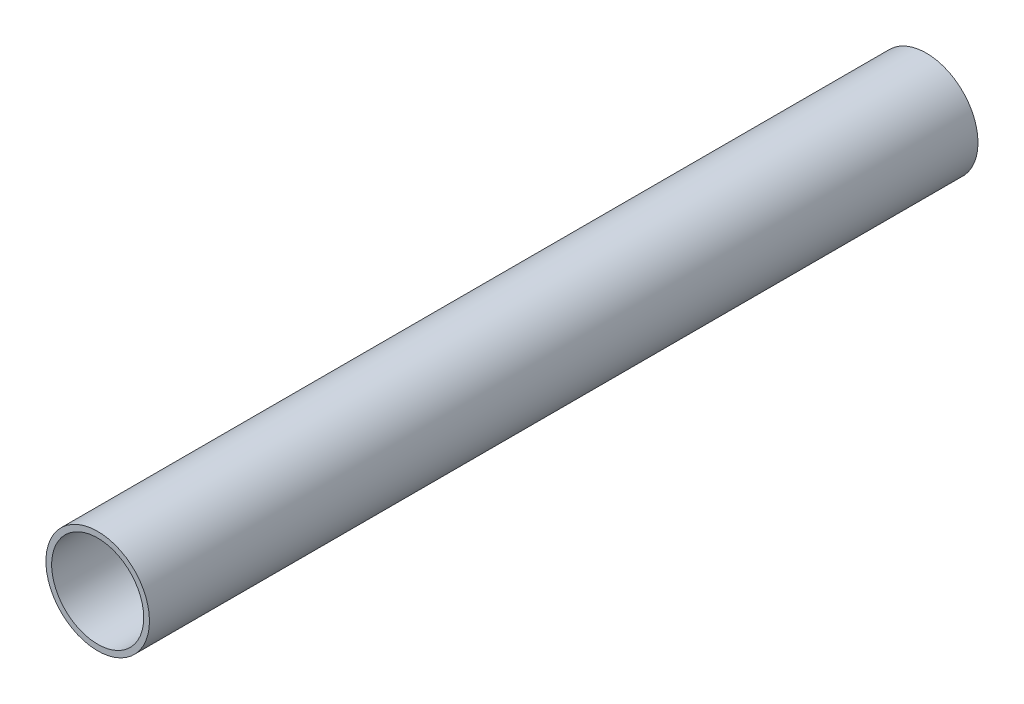
SolidWorks part; units mm, degrees
ref_plane "Front Plane" through (0, 0, 0) normal (0, 0, 1) x (1, 0, 0)
ref_plane "Top Plane" through (0, 0, 0) normal (0, 1, 0) x (1, 0, 0)
ref_plane "Right Plane" through (0, 0, 0) normal (1, 0, 0) x (0, 0, -1)
sketch "Sketch1" plane through (0, 0, 0) normal (0, 0, 1) x (1, 0, 0)
  circle A0 centre (0, 0) radius 12.7
  circle A1 centre (0, 0) radius 14.2875
  dimension "D1" = 25.4
  dimension "D2" = 28.575
extrude "Boss-Extrude1" add sketch "Sketch1" along normal blind 228.6
